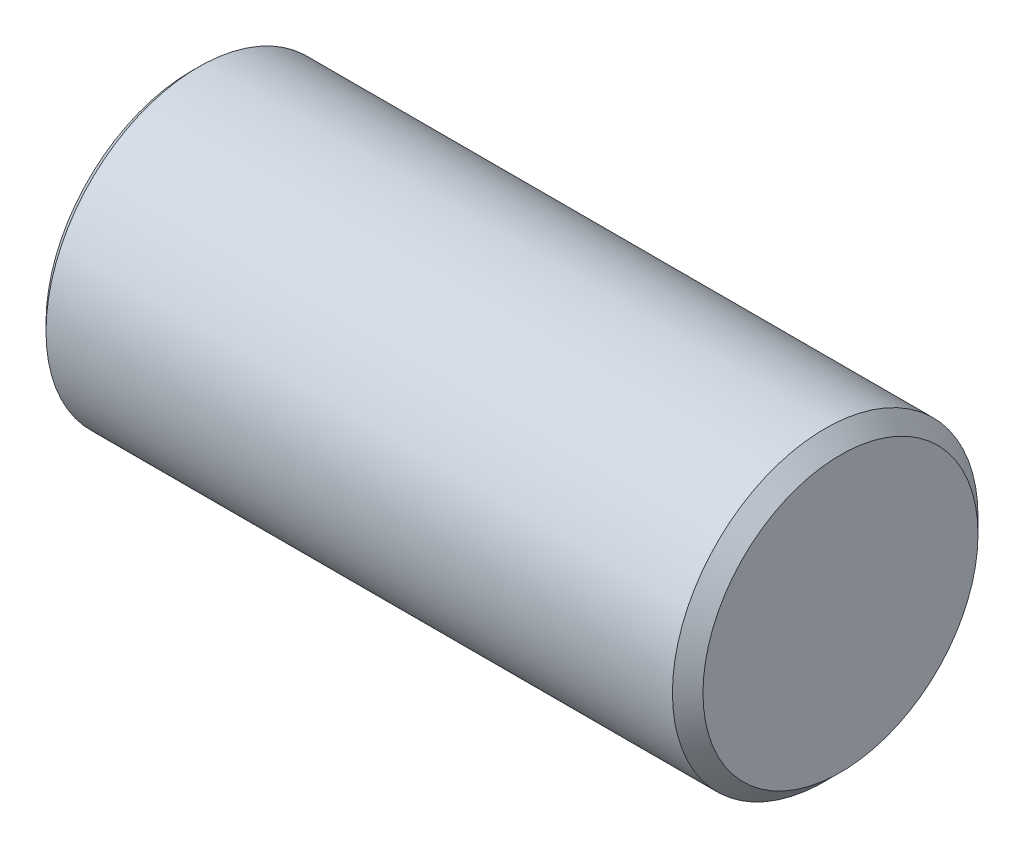
SolidWorks part; units mm, degrees
ref_plane "Спереди" through (0, 0, 0) normal (0, 0, 1) x (1, 0, 0)
ref_plane "Сверху" through (0, 0, 0) normal (0, 1, 0) x (1, 0, 0)
ref_plane "Справа" through (0, 0, 0) normal (1, 0, 0) x (0, 0, -1)
sketch "Эскиз1" plane through (0, 0, 0) normal (0, 1, 0) x (1, 0, 0)
  line L0 (92.6529, 0) -> (92.6529, 18)
  line L1 (90.6529, 20) -> (8.6529, 20)
  line L2 (7.6529, 19) -> (7.6529, 14.75)
  line L3 (7.6529, 14.75) -> (8.6529, 13.75)
  line L4 (76.7985, 0) -> (92.6529, 0)
  line L5 (102.994, 0) -> (-18.114, 0) construction
  line L6 (8.6529, 13.75) -> (71.6294, 13.75)
  line L7 (8.6529, 20) -> (7.6529, 19)
  line L8 (92.6529, 18) -> (90.6529, 20)
  line L9 (71.6294, 3.4302) -> (71.6294, 13.75)
  line L10 (71.6294, 3.4302) -> (76.7985, 0)
  point P1 (92.6529, 20)
  point P9 (7.6529, 20)
  point P10 (7.6529, 13.75)
  dimension "D1" = 1
  dimension "D2" = 45
  dimension "D3" = 1
  dimension "D4" = 45
  dimension "D5" = 2
  dimension "D6" = 45
  dimension "D7" = 6.25
revolve "Повернуть4" add sketch "Эскиз1" angle 360 about L5
